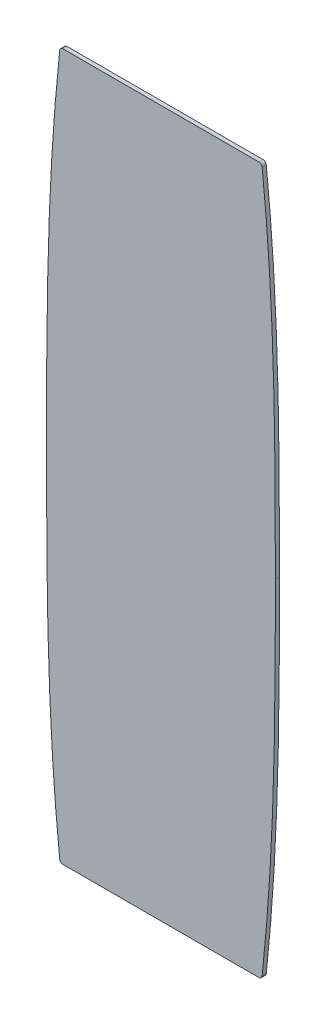
SolidWorks part; units mm, degrees
ref_plane "Front" through (0, 0, 0) normal (0, 0, 1) x (1, 0, 0)
ref_plane "Top" through (0, 0, 0) normal (0, 1, 0) x (1, 0, 0)
ref_plane "Right" through (0, 0, 0) normal (1, 0, 0) x (0, 0, -1)
sketch "Sketch1" plane through (0, 0, 0) normal (0, 0, 1) x (1, 0, 0)
  line L4 (-23.7959, -85.8) -> (23.7959, -85.8)
  line L5 (23.7959, 85.8) -> (-23.7959, 85.8)
  line L6 (-23.7959, -85.8) -> (23.7959, -85.8)
  line L7 (23.7959, 85.8) -> (-23.7959, 85.8)
  arc A8 (-24.5914, -85.0845) -> (-23.7959, -85.8) centre (-23.7959, -85) ccw
  arc A9 (23.7959, -85.8) -> (24.5914, -85.0845) centre (23.7959, -85) ccw
  arc A10 (24.5914, 85.0845) -> (23.7959, 85.8) centre (23.7959, 85) ccw
  arc A11 (-23.7959, 85.8) -> (-24.5914, 85.0845) centre (-23.7959, 85) ccw
  arc A12 (-24.5914, -85.0845) -> (-23.7959, -85.8) centre (-23.7959, -85) ccw
  arc A13 (23.7959, -85.8) -> (24.5914, -85.0845) centre (23.7959, -85) ccw
  arc A14 (24.5914, 85.0845) -> (23.7959, 85.8) centre (23.7959, 85) ccw
  arc A15 (-23.7959, 85.8) -> (-24.5914, 85.0845) centre (-23.7959, 85) ccw
  spline S8 degree 3 poles (-1813.6816, 775.3598) (38.2333, 514.2293) (-30.0727, 246.34) (-27.6629, -28.4006) (-27.5516, -35.4997) (-27.1348, -49.6946) (-26.8273, -56.7856) (-26.1559, -67.4085) (-25.8975, -70.9473) (6.4902, -456.0387) (490.043, -808.3332) (1630.7339, -1118.0367) knots -9.173904 -9.173904 -9.173904 -9.173904 0.25 0.25 0.5 0.5 0.75 0.75 0.875 0.875 14.362474 14.362474 14.362474 14.362474 only from (-27.8, 0) to (-24.5914, -85.0845)
  spline S9 degree 3 poles (-1805.145, -773.4019) (-243.2141, -617.0736) (8.2656, -350.3027) (26.8287, -56.7783) (27.1351, -49.686) (27.5518, -35.4924) (27.663, -28.3946) (30.0742, 246.5954) (-38.347, 515.2438) (1818.5454, 763.3075) knots -9.855908 -9.855908 -9.855908 -9.855908 0.25 0.25 0.5 0.5 0.75 0.75 10.184999 10.184999 10.184999 10.184999 only from (24.5914, -85.0845) to (27.8, 0)
  spline S10 degree 3 poles (1813.6816, -775.3598) (-38.2333, -514.2293) (30.0727, -246.34) (27.6629, 28.4006) (27.5516, 35.4997) (27.1348, 49.6946) (26.8273, 56.7856) (26.1559, 67.4085) (25.8975, 70.9473) (-6.4902, 456.0387) (-490.043, 808.3332) (-1630.7339, 1118.0367) knots -9.173904 -9.173904 -9.173904 -9.173904 0.25 0.25 0.5 0.5 0.75 0.75 0.875 0.875 14.362474 14.362474 14.362474 14.362474 only from (27.8, 0) to (24.5914, 85.0845)
  spline S11 degree 3 poles (1805.145, 773.4019) (243.2141, 617.0736) (-8.2656, 350.3027) (-26.8287, 56.7783) (-27.1351, 49.686) (-27.5518, 35.4924) (-27.663, 28.3946) (-30.0742, -246.5954) (38.347, -515.2438) (-1818.5454, -763.3075) knots -9.855908 -9.855908 -9.855908 -9.855908 0.25 0.25 0.5 0.5 0.75 0.75 10.184999 10.184999 10.184999 10.184999 only from (-24.5914, 85.0845) to (-27.8, 0)
  spline S12 degree 3 poles (-27.8, 0) (-27.8, -7.1003) (-27.7874, -14.2005) (-27.6629, -28.4006) (-27.5516, -35.4997) (-27.1348, -49.6946) (-26.8273, -56.7856) (-26.1559, -67.4085) (-25.8975, -70.9473) (-25.3027, -78.0197) (-24.9665, -81.5533) (-24.5914, -85.0845) knots 0 0 0 0 0.25 0.25 0.5 0.5 0.75 0.75 0.875 0.875 1 1 1 1
  spline S13 degree 3 poles (24.5914, -85.0845) (25.3415, -78.024) (25.9324, -70.9502) (26.8287, -56.7783) (27.1351, -49.686) (27.5518, -35.4924) (27.663, -28.3946) (27.7874, -14.1979) (27.8, -7.099) (27.8, 0) knots 0 0 0 0 0.25 0.25 0.5 0.5 0.75 0.75 1 1 1 1
  spline S14 degree 3 poles (27.8, 0) (27.8, 7.1003) (27.7874, 14.2005) (27.6629, 28.4006) (27.5516, 35.4997) (27.1348, 49.6946) (26.8273, 56.7856) (26.1559, 67.4085) (25.8975, 70.9473) (25.3027, 78.0197) (24.9665, 81.5533) (24.5914, 85.0845) knots 0 0 0 0 0.25 0.25 0.5 0.5 0.75 0.75 0.875 0.875 1 1 1 1
  spline S15 degree 3 poles (-24.5914, 85.0845) (-25.3415, 78.024) (-25.9324, 70.9502) (-26.8287, 56.7783) (-27.1351, 49.686) (-27.5518, 35.4924) (-27.663, 28.3946) (-27.7874, 14.1979) (-27.8, 7.099) (-27.8, 0) knots 0 0 0 0 0.25 0.25 0.5 0.5 0.75 0.75 1 1 1 1
  dimension "D1" = 0.2
extrude "Boss-Extrude1" add sketch "Sketch1" along normal up to surface (1 mm away)
sketch "Sketch2" plane through (0, 0, 1) normal (0, 0, 1) x (1, 0, 0)
  line L1 (-7.3, -60.5) -> (7.3, -60.5)
  line L2 (-7.3, -60.5) -> (-7.3, 15)
  line L3 (-7.3, 15) -> (7.3, 15)
  line L4 (7.3, -60.5) -> (7.3, 15)
  line L5 (-7.3, -60.5) -> (7.3, 15) construction
  line L6 (-7.3, 15) -> (7.3, -60.5) construction
  point P4 (0, -22.75)
